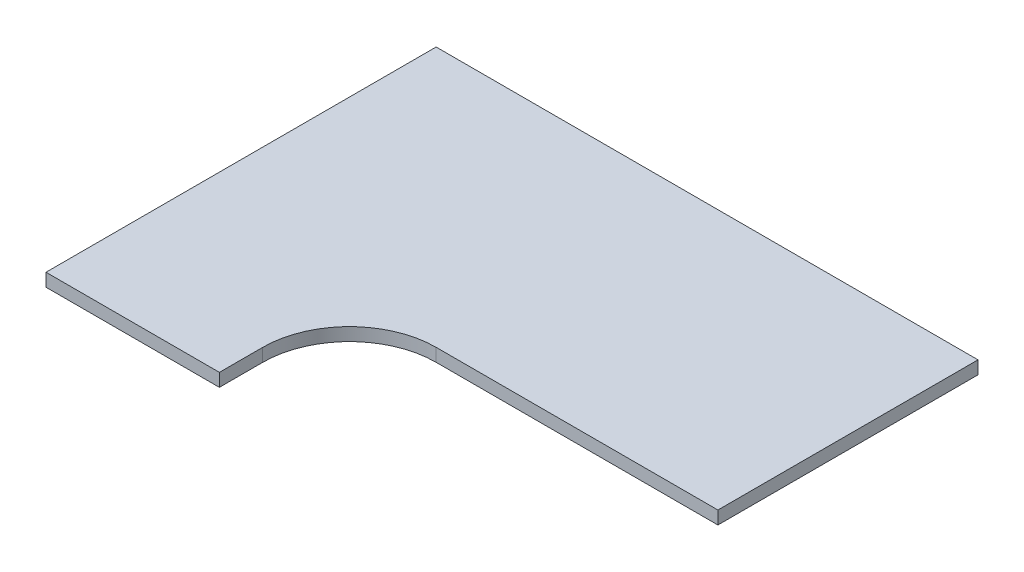
SolidWorks part; units mm, degrees
ref_plane "Front Plane" through (0, 0, 0) normal (0, 0, 1) x (1, 0, 0)
ref_plane "Top Plane" through (0, 0, 0) normal (0, 1, 0) x (1, 0, 0)
ref_plane "Right Plane" through (0, 0, 0) normal (1, 0, 0) x (0, 0, -1)
sketch "Sketch1" plane through (0, 0, 0) normal (0, 1, 0) x (1, 0, 0)
  line L0 (0, 0) -> (0, -900)
  line L1 (0, 0) -> (1250, 0)
  line L2 (1250, 0) -> (1250, -600)
  line L3 (1250, -600) -> (600, -600)
  line L4 (400, -800) -> (400, -900)
  line L5 (400, -900) -> (0, -900)
  arc A0 (600, -600) -> (400, -800) centre (600, -800) ccw
  dimension "D5" = 200
  dimension "D1" = 900
  dimension "D2" = 1250
  dimension "D3" = 600
  dimension "D4" = 400
extrude "Boss-Extrude1" add sketch "Sketch1" along normal blind 30
